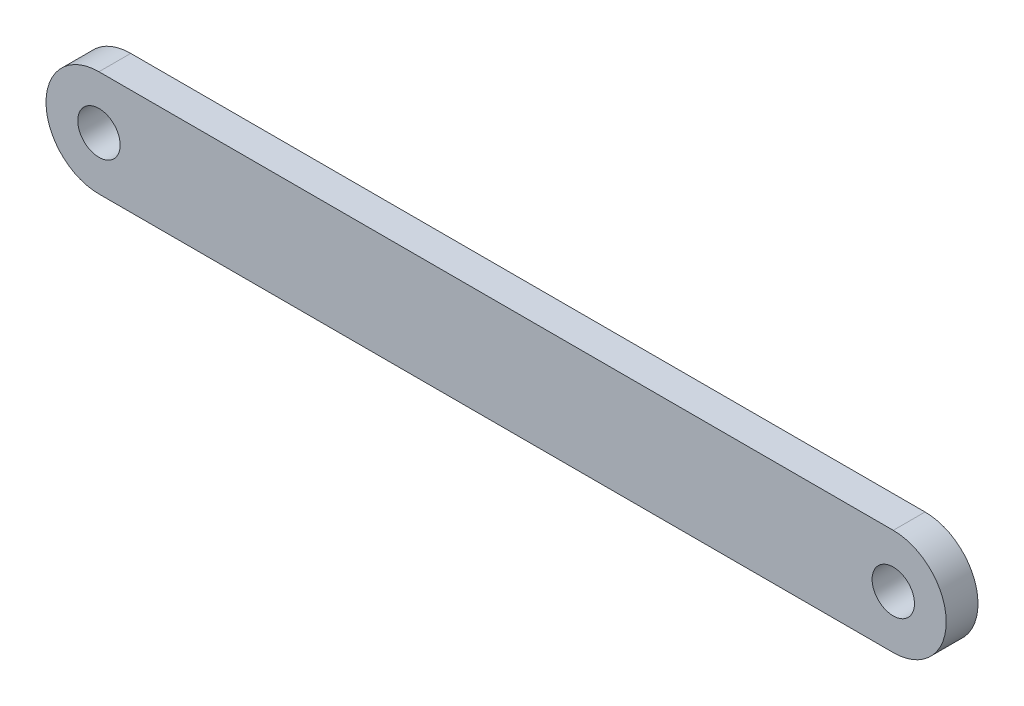
SolidWorks part; units mm, degrees
ref_plane "Front Plane" through (0, 0, 0) normal (0, 0, 1) x (1, 0, 0)
ref_plane "Top Plane" through (0, 0, 0) normal (0, 1, 0) x (1, 0, 0)
ref_plane "Right Plane" through (0, 0, 0) normal (1, 0, 0) x (0, 0, -1)
sketch "Sketch1" plane through (0, 0, 0) normal (0, 0, 1) x (1, 0, 0)
  line L1 (120.0787, 190.0323) -> (195.0787, 190.0323)
  line L3 (120.0787, 200.0323) -> (195.0787, 200.0323)
  arc A0 (120.0787, 200.0323) -> (120.0787, 190.0323) centre (120.0787, 195.0323) ccw
  arc A1 (195.0787, 200.0323) -> (195.0787, 190.0323) centre (195.0787, 195.0323) cw
  circle A2 centre (120.0787, 195.0323) radius 2
  circle A3 centre (195.0787, 195.0323) radius 2
  dimension "D3" = 4
  dimension "D4" = 4
  dimension "D1" = 75
  dimension "D2" = 10
extrude "Boss-Extrude1" add sketch "Sketch1" along normal blind 3
